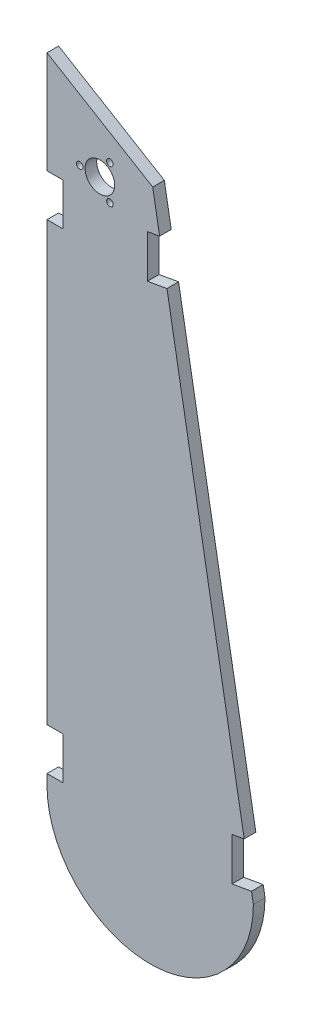
SolidWorks part; units mm, degrees
material "段ﾎﾞｰﾙ紙"
ref_plane "正面" through (0, 0, 0) normal (0, 0, 1) x (1, 0, 0)
ref_plane "平面" through (0, 0, 0) normal (0, 1, 0) x (1, 0, 0)
ref_plane "右側面" through (0, 0, 0) normal (1, 0, 0) x (0, 0, -1)
sketch "ｽｹｯﾁ1" plane through (0, 0, 0) normal (0, 0, 1) x (1, 0, 0)
  line L0 (0, 0) -> (0, 300)
  line L1 (0, 300) -> (50, 270)
  line L2 (50, 270) -> (97.6083, 0)
  arc A0 (0, 0) -> (97.6083, 0) centre (48.8041, 0) ccw
  dimension "D1" = 300
  dimension "D2" = 50
  dimension "D4" = 30
  dimension "D3" = 10
extrude "ﾎﾞｽ - 押し出し1" add sketch "ｽｹｯﾁ1" along normal blind 5.5 contours L2 A0 L0 L1
ref_plane "平面1" through (0, 0, -5) normal (0, 0, -1) x (-1, 0, 0)
sketch "ｽｹｯﾁ2" plane through (0, 0, -5) normal (0, 0, -1) x (-1, 0, 0)
  line L0 (0, 14.7923) -> (-95, 14.7923) construction
  line L1 (0, 0) -> (0, 300) construction
  line L2 (-50, 270) -> (-97.6083, 0) construction
  line L3 (0, 241.6436) -> (-55, 241.6436) construction
  point P0 (-48.8041, 0)
  point P5 (-47.5, 241.6436)
  point P11 (-7.5, 241.6436)
  point P12 (-87.5, 14.7923)
  point P13 (-7.5, 14.7923)
  dimension "D1" = 7.5
  dimension "D2" = 7.5
  dimension "D3" = 7.5
  dimension "D4" = 7.5
  dimension "D5" = 80
  dimension "D6" = 40
sketch "ｽｹｯﾁ3" plane through (0, 0, -5) normal (0, 0, -1) x (-1, 0, 0)
  line L0 (-95, 14.7923) -> (-55, 241.6436) construction
  line L1 (0, 14.7923) -> (0, 241.6436) construction
  line L2 (0, 14.7923) -> (0, -0.2077) construction
  line L3 (-95, 14.7923) -> (-97.6047, 0.0202) construction
  dimension "D1" = 15
  dimension "D2" = 15
sketch "ｽｹｯﾁ4" plane through (0, 0, 0) normal (0, 0, -1) x (-1, 0, 0)
  line L0 (0, 0) -> (0, 300) construction
  line L1 (0, 241.6436) -> (-55, 241.6436) construction
  circle A0 centre (-25, 261.6436) radius 9.5 construction
  point P0 (-25, 261.6436)
  point P7 (-15.5, 261.6436)
  point P9 (0, 0)
  dimension "D3" = 19
  dimension "D1" = 25
  dimension "D2" = 20
sketch "ｽｹｯﾁ5" plane through (0, 0, 0) normal (0, 0, -1) x (-1, 0, 0)
  circle A0 centre (-25, 261.6436) radius 7
  dimension "D1" = 14
extrude "ｶｯﾄ - 押し出し1" cut sketch "ｽｹｯﾁ5" against normal through all
sketch "ｽｹｯﾁ6" plane through (0, 0, 0) normal (0, 0, -1) x (-1, 0, 0)
  circle A0 centre (-15.5, 261.6436) radius 1.55
  dimension "D1" = 3.1
extrude "ｶｯﾄ - 押し出し2" cut sketch "ｽｹｯﾁ6" against normal through all
pattern_circular "円形ﾊﾟﾀｰﾝ1" count 3 every 120 about axis through (25, 261.6436, 0) along (0, 0, 1) of "ｶｯﾄ - 押し出し2"
sketch "ｽｹｯﾁ7" plane through (0, 0, 0) normal (0, 0, -1) x (-1, 0, 0)
  line L0 (0, 4.7923) -> (0, 24.7923)
  line L1 (0, 14.7923) -> (0, 241.6436) construction
  line L2 (0, 4.7923) -> (-7.5, 4.7923)
  line L3 (-7.5, 4.7923) -> (-7.5, 24.7923)
  line L4 (-7.5, 24.7923) -> (0, 24.7923)
  point P6 (0, 14.7923)
  dimension "D1" = 20
  dimension "D2" = 7.5
extrude "ｶｯﾄ - 押し出し3" cut sketch "ｽｹｯﾁ7" against normal through all
sketch "ｽｹｯﾁ8" plane through (0, 0, -5) normal (0, 0, -1) x (-1, 0, 0)
  line L0 (0, 231.6436) -> (0, 251.6436)
  line L1 (0, 251.6436) -> (-7.5, 251.6436)
  line L2 (-7.5, 251.6436) -> (-7.5, 231.6436)
  line L3 (-7.5, 231.6436) -> (0, 231.6436)
  point P5 (0, 241.6436)
  dimension "D1" = 20
  dimension "D2" = 7.5
extrude "ｶｯﾄ - 押し出し4" cut sketch "ｽｹｯﾁ8" against normal through all
sketch "ｽｹｯﾁ9" plane through (0, 0, -5) normal (0, 0, -1) x (-1, 0, 0)
  line L0 (-96.7365, 4.9442) -> (-93.2635, 24.6404)
  line L1 (-93.2635, 24.6404) -> (-87.5, 23.6241)
  line L2 (-87.5, 23.6241) -> (-87.5, 3.3156)
  line L3 (-87.5, 3.3156) -> (-96.7365, 4.9442)
  line L4 (0, 14.7923) -> (-95, 14.7923) construction
  line L5 (-95, 14.7923) -> (-55, 241.6436) construction
  point P4 (-95, 14.7923)
  dimension "D1" = 20
extrude "ｶｯﾄ - 押し出し5" cut sketch "ｽｹｯﾁ9" against normal through all contours L3 L0 L1 L2
sketch "ｽｹｯﾁ10" plane through (0, 0, -5) normal (0, 0, -1) x (-1, 0, 0)
  line L0 (-53.2635, 251.4917) -> (-56.7365, 231.7955)
  line L1 (-50, 270) -> (-93.2635, 24.6404) construction
  line L2 (-53.2635, 251.4917) -> (-47.5, 250.4754)
  line L3 (-47.5, 250.4754) -> (-47.5, 230.1669)
  line L4 (-47.5, 230.1669) -> (-56.7365, 231.7955)
  point P4 (-55, 241.6436)
  dimension "D1" = 20
extrude "ｶｯﾄ - 押し出し6" cut sketch "ｽｹｯﾁ10" against normal through all
